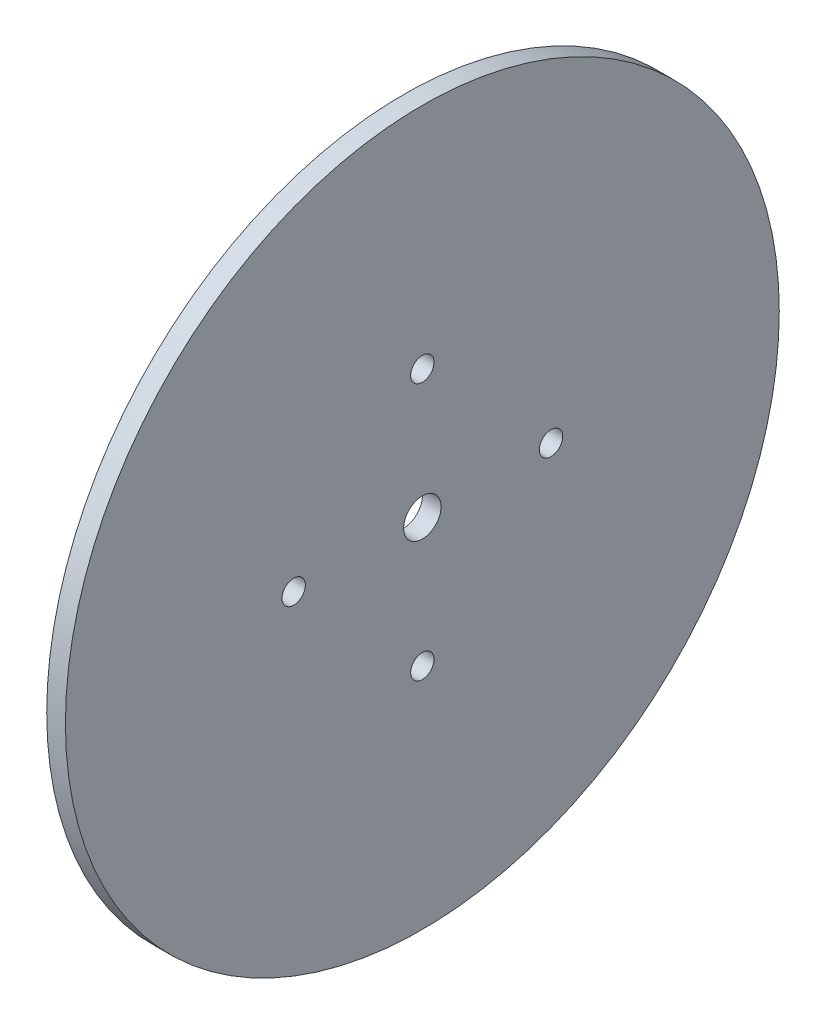
SolidWorks part; units mm, degrees
ref_plane "Front Plane" through (0, 0, 0) normal (0, 0, 1) x (1, 0, 0)
ref_plane "Top Plane" through (0, 0, 0) normal (0, 1, 0) x (1, 0, 0)
ref_plane "Right Plane" through (0, 0, 0) normal (1, 0, 0) x (0, 0, -1)
sketch "Sketch1" plane through (0, 0, 0) normal (1, 0, 0) x (0, 0, -1)
  line L0 (-76.29, 0) -> (76.29, 0) construction
  line L1 (0, 76.29) -> (0, -76.29) construction
  circle A0 centre (0, 0) radius 76.29
  circle A1 centre (0, 27.5) radius 2.5
  circle A2 centre (27.5, 0) radius 2.5
  circle A3 centre (0, -27.5) radius 2.5
  circle A4 centre (-27.5, 0) radius 2.5
  circle A5 centre (0, 0) radius 4
  point P11 (0, 0)
  point P15 (0, 0)
  dimension "D1" = 152.58
  dimension "D2" = 5
  dimension "D3" = 55
  dimension "D4" = 4
extrude "Boss-Extrude1" add sketch "Sketch1" along normal blind 4
